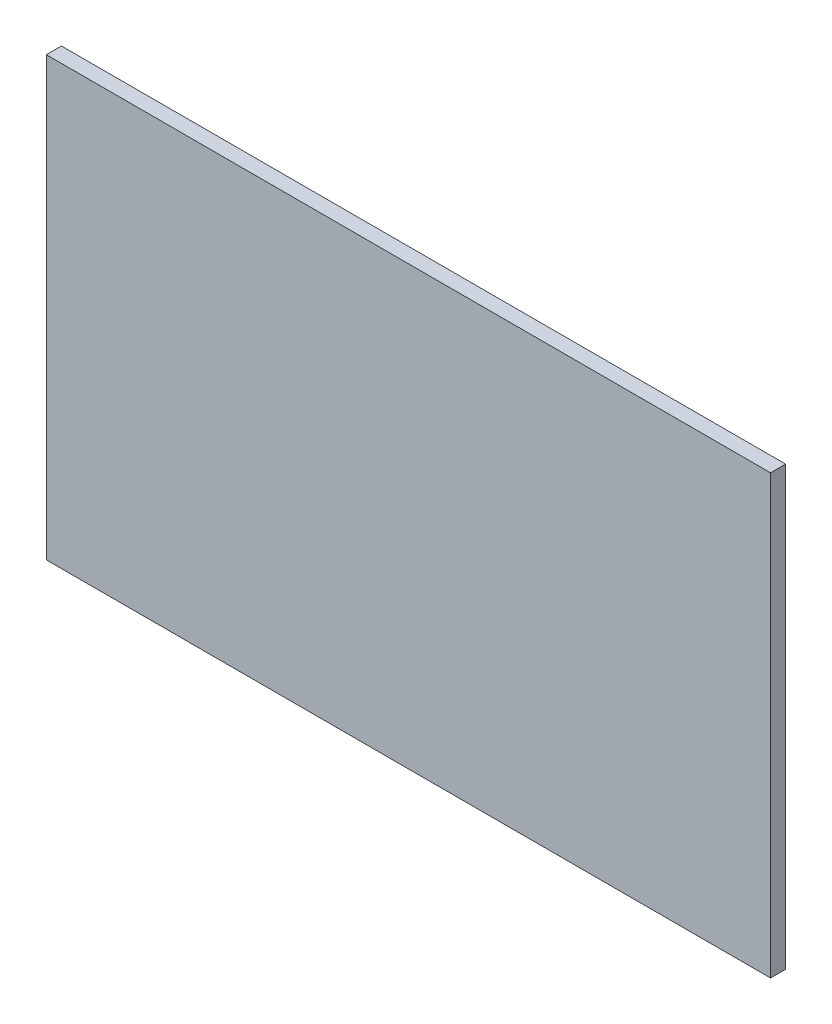
SolidWorks part; units mm, degrees
ref_plane "Plan de face" through (0, 0, 0) normal (0, 0, 1) x (1, 0, 0)
ref_plane "Plan de dessus" through (0, 0, 0) normal (0, 1, 0) x (1, 0, 0)
ref_plane "Plan de droite" through (0, 0, 0) normal (1, 0, 0) x (0, 0, -1)
sketch "Esquisse1" plane through (0, 0, 0) normal (0, 0, 1) x (1, 0, 0)
  line L1 (0, 0) -> (240, 0)
  line L2 (0, 0) -> (0, -145)
  line L3 (0, -145) -> (240, -145)
  line L4 (240, 0) -> (240, -145)
  dimension "D1" = 240
  dimension "D2" = 145
extrude "Boss.-Extru.1" add sketch "Esquisse1" along normal blind 5
